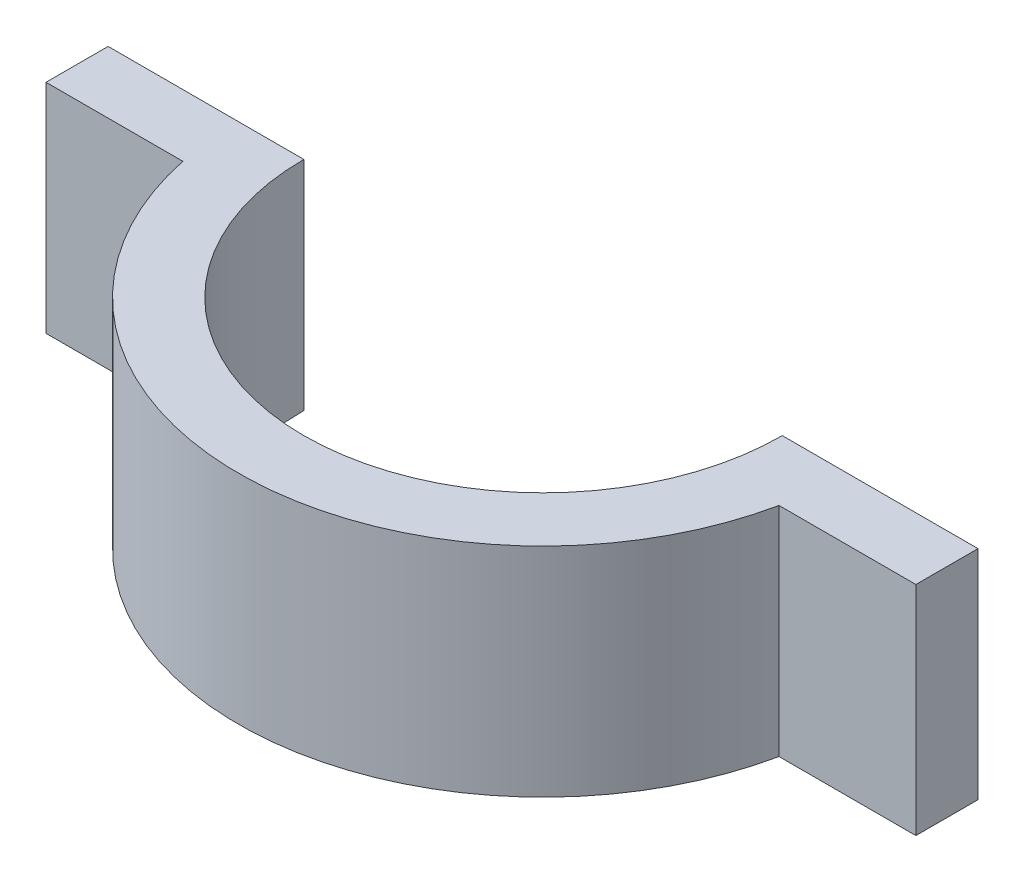
SolidWorks part; units mm, degrees
ref_plane "Front Plane" through (0, 0, 0) normal (0, 0, 1) x (1, 0, 0)
ref_plane "Top Plane" through (0, 0, 0) normal (0, 1, 0) x (1, 0, 0)
ref_plane "Right Plane" through (0, 0, 0) normal (1, 0, 0) x (0, 0, -1)
sketch "Sketch1" plane through (0, 0, 0) normal (0, 1, 0) x (1, 0, 0)
  line L0 (87.0289, 0) -> (-97.3953, 0)
  circle A0 centre (0, 0) radius 70
  circle A1 centre (0, 0) radius 55
  dimension "D1" = 140
  dimension "D2" = 110
extrude "Boss-Extrude1" add sketch "Sketch1" along normal blind 50 contours A1 L0 A0
sketch "Sketch3" plane through (0, 0, 0) normal (1, 0, 0) x (0, 0, -1)
  line L0 (0, 50) -> (-55, 50) construction
  line L1 (-14.2822, 50) -> (0, 50)
  line L2 (-14.2822, 50) -> (-14.2822, 0)
  line L3 (-14.2822, 0) -> (0, 0)
  line L4 (0, 50) -> (0, 0)
extrude "Boss-Extrude2" add sketch "Sketch3" along normal mid plane 200 contours L4 L3 L2 L1
sketch "Sketch4" plane through (0, 50, 0) normal (0, 1, 0) x (1, 0, 0)
  line L0 (-55, 0) -> (55, 0)
  circle A0 centre (0, 0) radius 55
extrude "Cut-Extrude1" cut sketch "Sketch4" against normal blind 200 contours A0
